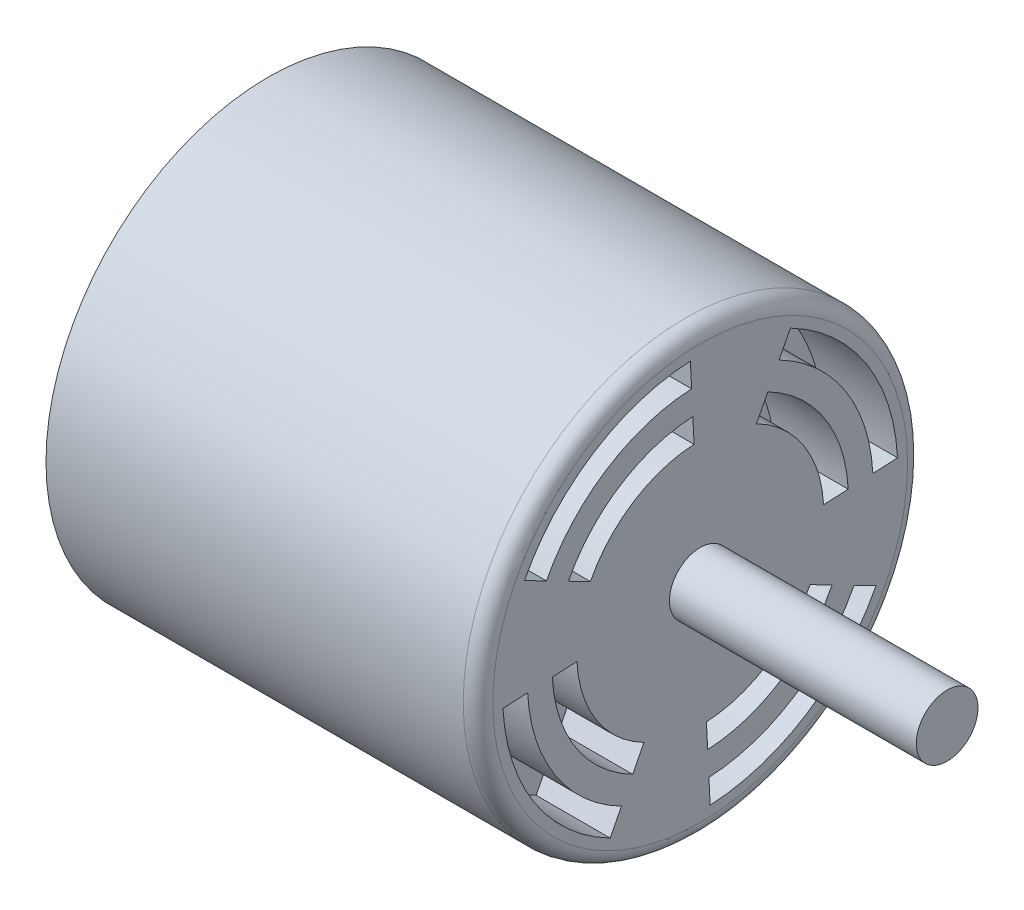
SolidWorks part; units mm, degrees
material "Alloy Steel"
ref_plane "Front Plane" through (0, 0, 0) normal (1, 0, 0) x (0, 1, 0)
ref_plane "Top Plane" through (0, 0, 0) normal (0, 0, 1) x (0, 1, 0)
ref_plane "Right Plane" through (0, 0, 0) normal (0, 1, 0) x (-1, 0, 0)
sketch "Sketch1" plane through (0, 0, 0) normal (1, 0, 0) x (0, 1, 0)
  circle A0 centre (0, 0) radius 22.86
  dimension "D1" = 45.72
extrude "Boss-Extrude1" add sketch "Sketch1" along normal blind 44.45
sketch "Sketch2" plane through (44.45, 0, 0) normal (1, 0, 0) x (0, 1, 0)
  circle A0 centre (0, 0) radius 3.175
  dimension "D1" = 6.35
extrude "Boss-Extrude2" add sketch "Sketch2" along normal blind 25.4
sketch "Sketch3" plane through (44.45, 0, 0) normal (1, 0, 0) x (0, 1, 0)
  line L0 (12.6841, 0.6362) -> (15.2209, 0.7634)
  line L1 (5.7911, 11.3028) -> (6.9493, 13.5634)
  line L2 (17.7577, 0.8906) -> (20.2945, 1.0179)
  line L3 (8.1075, 15.8239) -> (9.2658, 18.0845)
  line L4 (15.8239, -8.1075) -> (18.0845, -9.2658)
  line L5 (11.3028, -5.7911) -> (13.5634, -6.9493)
  line L6 (0.6362, -12.6841) -> (0.7634, -15.2209)
  line L7 (0.8906, -17.7577) -> (1.0179, -20.2945)
  line L8 (-8.1075, -15.8239) -> (-9.2658, -18.0845)
  line L9 (-5.7911, -11.3028) -> (-6.9493, -13.5634)
  line L10 (-12.6841, -0.6362) -> (-15.2209, -0.7634)
  line L11 (-17.7577, -0.8906) -> (-20.2945, -1.0179)
  line L12 (-15.8239, 8.1075) -> (-18.0845, 9.2658)
  line L13 (-11.3028, 5.7911) -> (-13.5634, 6.9493)
  line L14 (-0.6362, 12.6841) -> (-0.7634, 15.2209)
  line L15 (-0.8906, 17.7577) -> (-1.0179, 20.2945)
  arc A0 (12.6841, 0.6362) -> (5.7911, 11.3028) centre (0, 0) ccw
  arc A1 (15.2209, 0.7634) -> (6.9493, 13.5634) centre (0, 0) ccw
  arc A2 (20.2945, 1.0179) -> (9.2658, 18.0845) centre (0, 0) ccw
  arc A3 (17.7577, 0.8906) -> (8.1075, 15.8239) centre (0, 0) ccw
  circle A4 centre (0, 0) radius 12.7 construction
  circle A5 centre (0, 0) radius 15.24 construction
  circle A6 centre (0, 0) radius 17.78 construction
  circle A7 centre (0, 0) radius 20.32 construction
  arc A8 (0.7634, -15.2209) -> (13.5634, -6.9493) centre (0, 0) ccw
  arc A9 (0.8906, -17.7577) -> (15.8239, -8.1075) centre (0, 0) ccw
  arc A10 (1.0179, -20.2945) -> (18.0845, -9.2658) centre (0, 0) ccw
  arc A11 (0.6362, -12.6841) -> (11.3028, -5.7911) centre (0, 0) ccw
  arc A12 (-15.2209, -0.7634) -> (-6.9493, -13.5634) centre (0, 0) ccw
  arc A13 (-17.7577, -0.8906) -> (-8.1075, -15.8239) centre (0, 0) ccw
  arc A14 (-20.2945, -1.0179) -> (-9.2658, -18.0845) centre (0, 0) ccw
  arc A15 (-12.6841, -0.6362) -> (-5.7911, -11.3028) centre (0, 0) ccw
  arc A16 (-0.7634, 15.2209) -> (-13.5634, 6.9493) centre (0, 0) ccw
  arc A17 (-0.8906, 17.7577) -> (-15.8239, 8.1075) centre (0, 0) ccw
  arc A18 (-1.0179, 20.2945) -> (-18.0845, 9.2658) centre (0, 0) ccw
  arc A19 (-0.6362, 12.6841) -> (-11.3028, 5.7911) centre (0, 0) ccw
  point P44 (0, 0)
  dimension "D1" = 25.4
  dimension "D5" = 60
  dimension "D2" = 2.54
  dimension "D3" = 7.62
  dimension "D4" = 5.08
  dimension "D6" = 4
extrude "Cut-Extrude1" cut sketch "Sketch3" against normal blind 7.62
fillet "Fillet1" radius 1.524 1 edges at (44.45, 0, -22.86)
